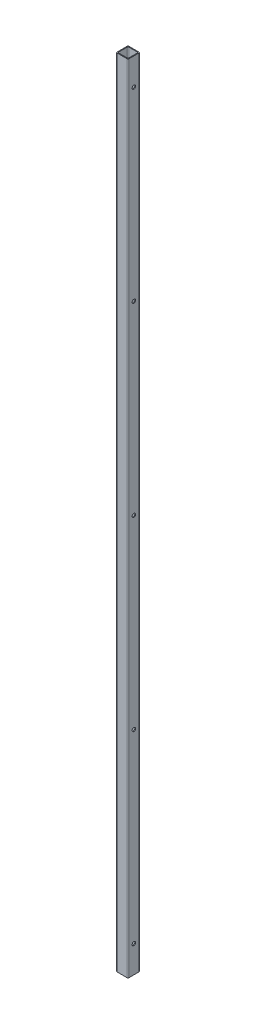
SolidWorks part; units mm, degrees
ref_plane "Front Plane" through (0, 0, 0) normal (0, 0, 1) x (1, 0, 0)
ref_plane "Top Plane" through (0, 0, 0) normal (0, 1, 0) x (1, 0, 0)
ref_plane "Right Plane" through (0, 0, 0) normal (1, 0, 0) x (0, 0, -1)
sketch "Sketch1" plane through (0, 0, 0) normal (0, 1, 0) x (1, 0, 0)
  line L0 (8.382, -8.382) -> (8.382, 8.382)
  line L1 (-9.652, -9.652) -> (9.652, -9.652)
  line L2 (-9.652, -9.652) -> (-9.652, 9.652)
  line L3 (-9.652, 9.652) -> (9.652, 9.652)
  line L4 (9.652, -9.652) -> (9.652, 9.652)
  line L5 (-9.652, -9.652) -> (9.652, 9.652) construction
  line L6 (-9.652, 9.652) -> (9.652, -9.652) construction
  line L7 (-8.382, 8.382) -> (8.382, 8.382)
  line L8 (-8.382, -8.382) -> (-8.382, 8.382)
  line L9 (-8.382, -8.382) -> (8.382, -8.382)
  point P0 (0, 0)
  dimension "D1" = 19.304
  dimension "D2" = 1.27
extrude "Boss-Extrude1" add sketch "Sketch1" along normal blind 1308.1
fillet "Fillet1" radius 1.27 8 edges at (-9.652, 654.05, 9.652) (-9.652, 654.05, -9.652) (9.652, 654.05, -9.652) (9.652, 654.05, 9.652) (-8.382, 654.05, -8.382) (8.382, 654.05, 8.382) (8.382, 654.05, -8.382) (-8.382, 654.05, 8.382)
hole_wizard "#1 (0.228) Diameter Hole1" positions "Sketch2" profile "Sketch3" hole size "#1" standard "ANSI Inch" end condition through all
sketch "Sketch2" plane through (9.652, 0, 0) normal (1, 0, 0) x (0, 0, -1)
  line L0 (0, 1308.1) -> (0, 0) construction
  line L1 (-8.382, 1308.1) -> (8.382, 1308.1) construction
  point P8 (0, 1263.65)
  point P55 (0, 958.85)
  point P56 (0, 654.05)
  point P57 (0, 349.25)
  point P58 (0, 44.45)
  dimension "D1" = 44.45
  dimension "D2" = 5
sketch "Sketch3" plane through (9.652, 44.45, 0) normal (0, 1, 0) x (0, 0, -1)
  line L0 (0, 0) -> (0, 19.304)
  line L1 (0, 19.304) -> (2.8956, 19.304)
  line L2 (2.8956, 19.304) -> (2.8956, 0)
  line L5 (2.8956, 0) -> (0, 0)
  line L11 (0, -6.35) -> (0, 107.95) construction
  dimension "Thru Hole Dia." = 5.7912
  dimension "Thru Hole Depth" = 19.304
